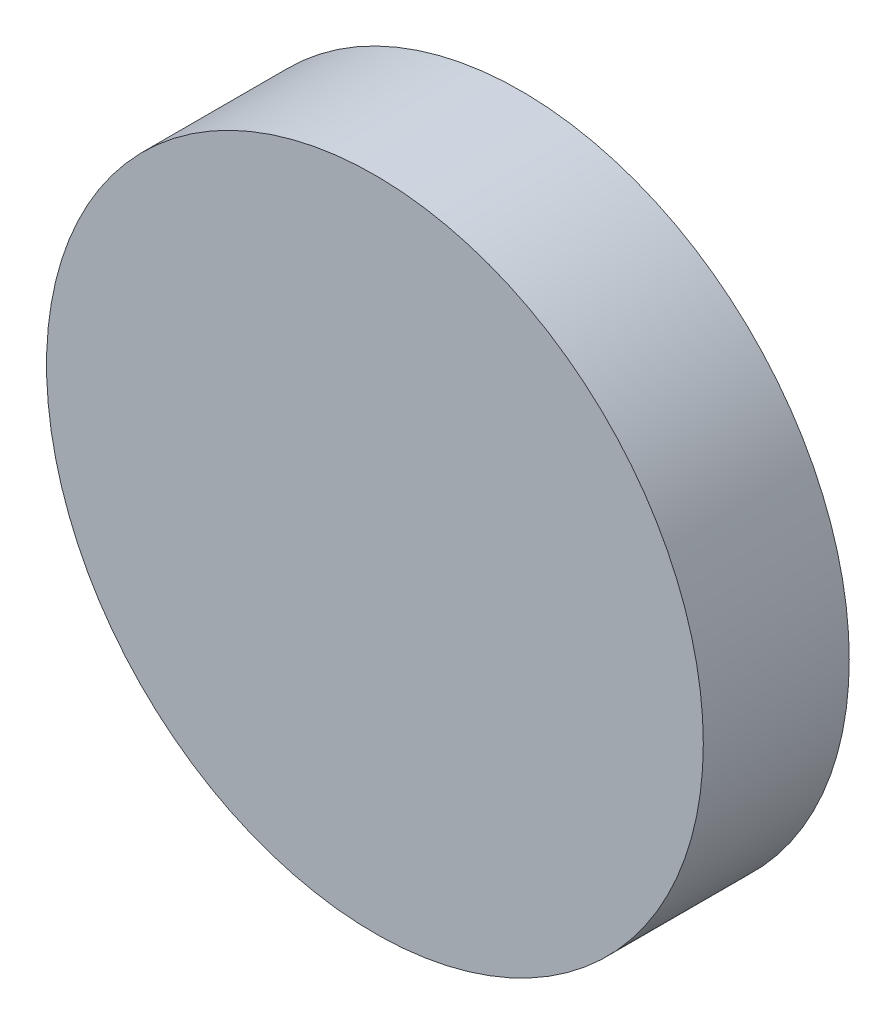
SolidWorks part; units mm, degrees
ref_plane "Front Plane" through (0, 0, 0) normal (0, 0, 1) x (1, 0, 0)
ref_plane "Top Plane" through (0, 0, 0) normal (0, 1, 0) x (1, 0, 0)
ref_plane "Right Plane" through (0, 0, 0) normal (1, 0, 0) x (0, 0, -1)
other "Configuration Table"
sketch "Sketch1" plane through (0, 0, 0) normal (0, 0, 1) x (1, 0, 0)
  circle A0 centre (700, 1450) radius 90
extrude "STORE_evap_fan_1" add sketch "Sketch1" against normal blind 40 from offset 750 separate body
